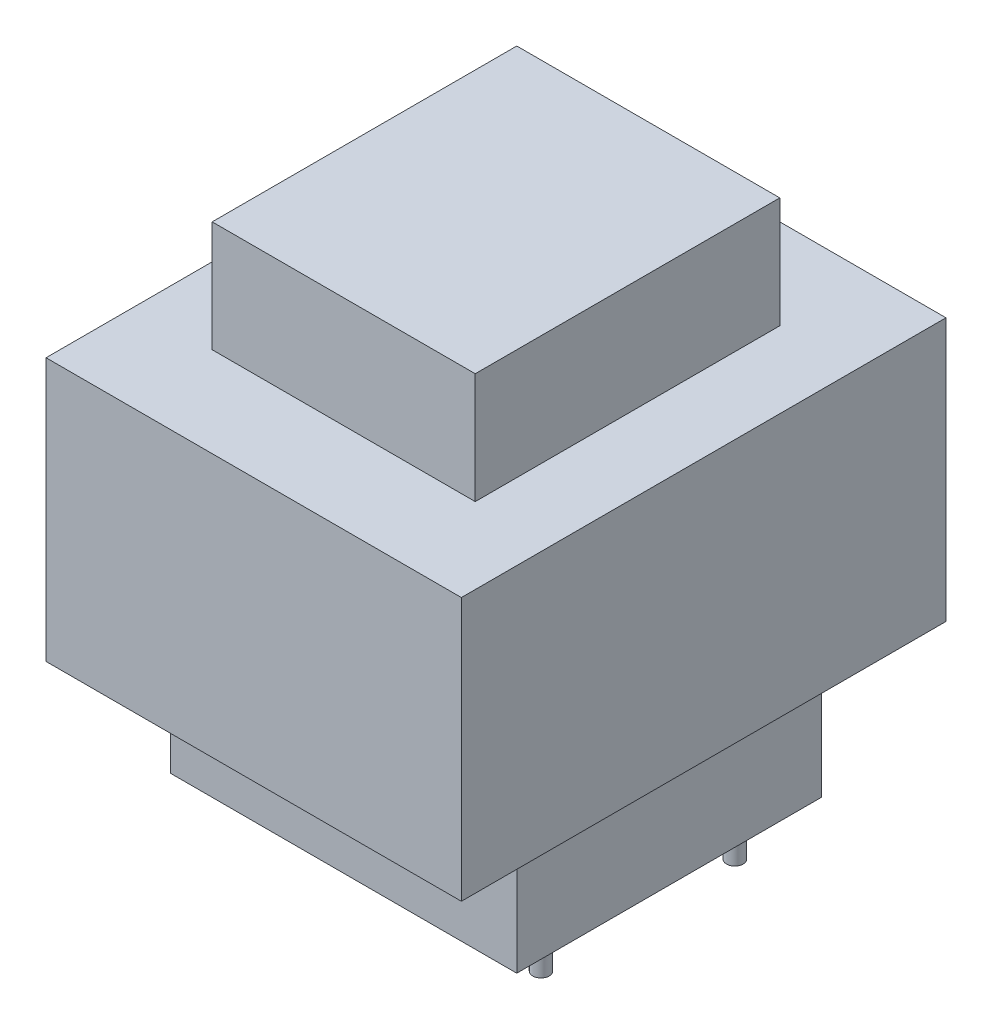
SolidWorks part; units mm, degrees
ref_plane "Спереди" through (0, 0, 0) normal (0, 0, 1) x (1, 0, 0)
ref_plane "Сверху" through (0, 0, 0) normal (0, 1, 0) x (1, 0, 0)
ref_plane "Справа" through (0, 0, 0) normal (1, 0, 0) x (0, 0, -1)
sketch "Эскиз1" plane through (0, 0, 0) normal (0, 1, 0) x (1, 0, 0)
  line L1 (-12.5, -11) -> (12.5, -11)
  line L2 (-12.5, -11) -> (-12.5, 11)
  line L3 (-12.5, 11) -> (12.5, 11)
  line L4 (12.5, -11) -> (12.5, 11)
  line L5 (-12.5, -11) -> (12.5, 11) construction
  line L6 (-12.5, 11) -> (12.5, -11) construction
  point P0 (0, 0)
extrude "Бобышка-Вытянуть1" add sketch "Эскиз1" along normal blind 9
sketch "Эскиз2" plane through (0, 9, 0) normal (0, 1, 0) x (1, 0, 0)
  line L1 (-9.5, -11) -> (9.5, -11)
  line L2 (-9.5, -11) -> (-9.5, 11)
  line L3 (-9.5, 11) -> (9.5, 11)
  line L4 (9.5, -11) -> (9.5, 11)
  line L5 (-9.5, -11) -> (9.5, 11) construction
  line L6 (-9.5, 11) -> (9.5, -11) construction
  point P0 (0, 0)
extrude "Бобышка-Вытянуть2" add sketch "Эскиз2" along normal blind 27
sketch "Эскиз3" plane through (0, 9, 0) normal (0, 1, 0) x (1, 0, 0)
  line L1 (15, -17.5) -> (-15, -17.5)
  line L2 (15, -17.5) -> (15, 17.5)
  line L3 (15, 17.5) -> (-15, 17.5)
  line L4 (-15, -17.5) -> (-15, 17.5)
  line L5 (15, -17.5) -> (-15, 17.5) construction
  line L6 (15, 17.5) -> (-15, -17.5) construction
  line L7 (9.5, -11) -> (-9.5, -11)
  line L8 (9.5, -11) -> (9.5, 11)
  line L9 (9.5, 11) -> (-9.5, 11)
  line L10 (-9.5, -11) -> (-9.5, 11)
  line L11 (9.5, -11) -> (-9.5, 11) construction
  line L12 (9.5, 11) -> (-9.5, -11) construction
  point P0 (0, 0)
  point P6 (0, 0)
sketch "Эскиз4" plane through (0, 0, 0) normal (0, -1, 0) x (1, 0, 0)
  line L1 (10.25, 7) -> (-10.25, 7) construction
  line L2 (10.25, 7) -> (10.25, -7) construction
  line L3 (10.25, -7) -> (-10.25, -7) construction
  line L4 (-10.25, 7) -> (-10.25, -7) construction
  line L5 (10.25, 7) -> (-10.25, -7) construction
  line L6 (10.25, -7) -> (-10.25, 7) construction
  circle A0 centre (10.25, -7) radius 0.6
  circle A1 centre (10.25, 7) radius 0.6
  circle A2 centre (-10.25, 7) radius 0.6
  circle A3 centre (-10.25, -7) radius 0.6
  circle A4 centre (-10.25, 0) radius 0.6
  point P0 (0, 0)
  point P12 (0, 7)
  point P13 (-10.25, 0)
  dimension "D1" = 20.5
  dimension "D2" = 14
extrude "Бобышка-Вытянуть4" add sketch "Эскиз4" along normal blind 3
extrude "Бобышка-Вытянуть6" add sketch "Эскиз3" along normal blind 19
